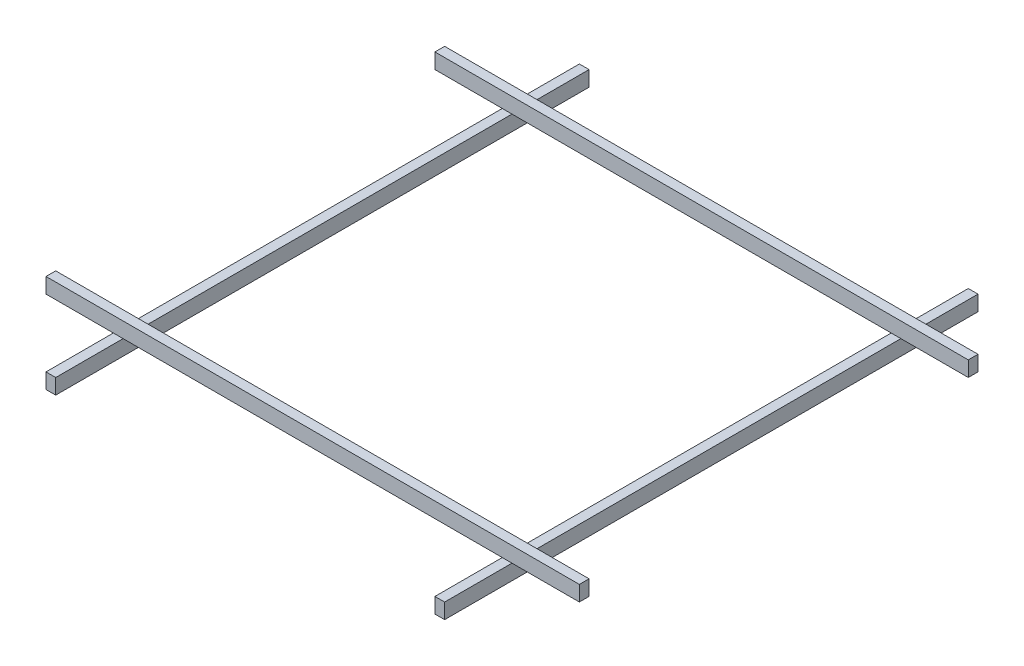
SolidWorks part; units mm, degrees
material "Doug Fir"
ref_plane "Front Plane" through (0, 0, 0) normal (0, 0, 1) x (1, 0, 0)
ref_plane "Top Plane" through (0, 0, 0) normal (0, 1, 0) x (1, 0, 0)
ref_plane "Right Plane" through (0, 0, 0) normal (1, 0, 0) x (0, 0, -1)
sketch "Lower Level" plane through (0, 0, 0) normal (0, 1, 0) x (1, 0, 0)
  line L0 (355.6, 0) -> (355.6, 4876.8)
  line L1 (3911.6, 0) -> (3911.6, 4876.8)
  line L2 (355.6, 2438.4) -> (3911.6, 2438.4) construction
  point P7 (2133.6, 2438.4)
  dimension "D1" = 4876.8
  dimension "D2" = 1778
ref_plane "Plane2" through (0, 139.7, 0) normal (0, 1, 0) x (1, 0, 0)
sketch "Sketch12" plane through (0, 139.7, 0) normal (0, 1, 0) x (1, 0, 0)
  line L0 (-304.8, 4216.4) -> (4572, 4216.4)
  line L1 (4572, 660.4) -> (-304.8, 660.4)
  line L2 (2133.6, 4216.4) -> (2133.6, 660.4) construction
  point P0 (2133.6, 2438.4)
  point P6 (2133.6, 660.4)
  point P7 (2133.6, 4216.4)
  point P10 (2133.6, 2438.4)
  dimension "D1" = 4876.8
  dimension "D2" = 1778
other "Profiles 4X6(1)"
ref_plane "Plane1" through (355.6, 0, 0) normal (0, 0, -1) x (-1, 0, 0)
sketch "Sketch1" plane through (355.6, 0, 0) normal (0, 0, -1) x (-1, 0, 0)
  line L1 (-44.45, 69.85) -> (44.45, 69.85)
  line L2 (-44.45, 69.85) -> (-44.45, -69.85)
  line L3 (-44.45, -69.85) -> (44.45, -69.85)
  line L4 (44.45, 69.85) -> (44.45, -69.85)
  line L5 (-44.45, 69.85) -> (44.45, -69.85) construction
  line L6 (-44.45, -69.85) -> (44.45, 69.85) construction
  point P0 (0, 0)
  point P6 (0, 69.85)
  point P7 (0, -69.85)
  point P8 (44.45, 0)
  point P9 (-44.45, 0)
  point P10 (0, 0)
  dimension "D1" = 88.9
  dimension "D2" = 139.7
sketch3d "3DSketch2"
  line L0 (2133.6, 139.7, -2438.4) -> (2133.6, 0, -2438.4)
  line L1 (355.6, 0, -2438.4) -> (3911.6, 0, -2438.4) construction
equation "\"Width\" = 70"
equation "\"Length\"=192"
equation "\"D1@Lower Level\"=\"Length\""
equation "\"D2@Lower Level\"=\"Width\""
equation "\"D1@Sketch12\"=\"Length\""
equation "\"D2@Sketch12\"=\"Width\""
